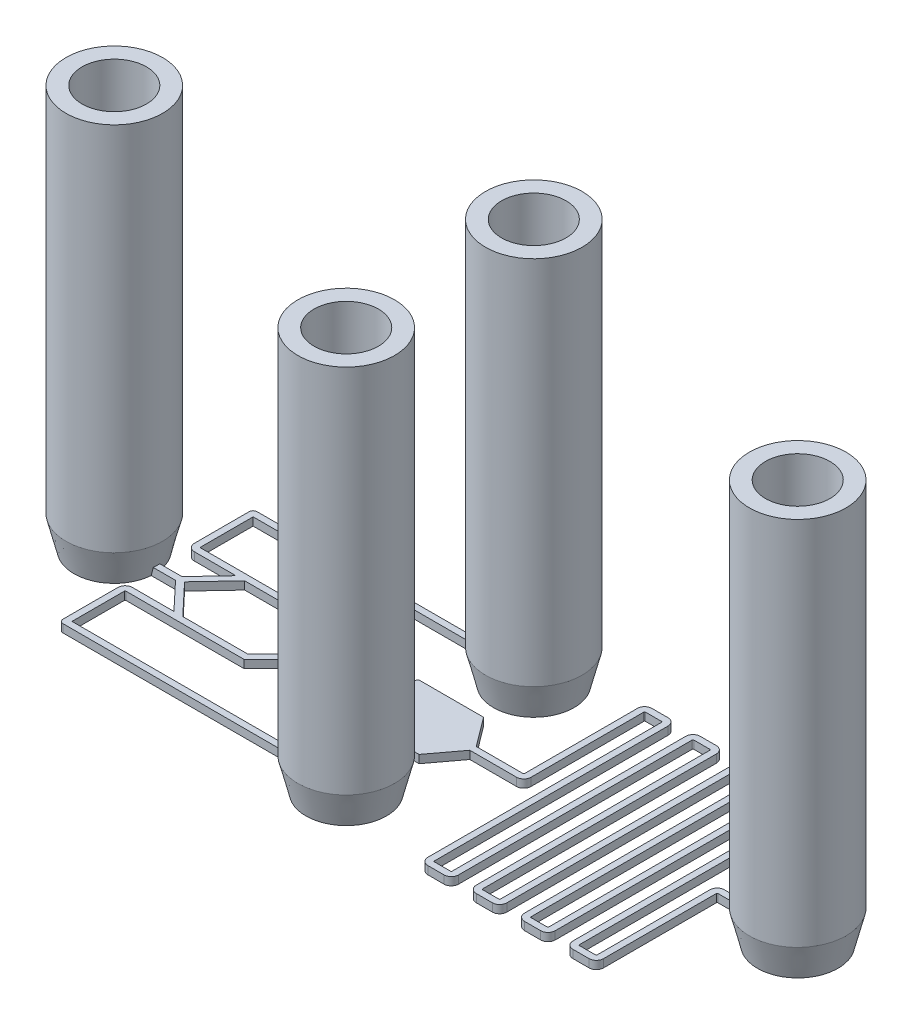
SolidWorks part; units mm, degrees
ref_plane "Front Plane" through (0, 0, 0) normal (0, 0, 1) x (1, 0, 0)
ref_plane "Top Plane" through (0, 0, 0) normal (0, 1, 0) x (1, 0, 0)
ref_plane "Right Plane" through (0, 0, 0) normal (1, 0, 0) x (0, 0, -1)
sketch "skelton" plane through (0, 0, 0) normal (0, 0, 1) x (1, 0, 0)
  line L0 (-100, 0) -> (100, 0) construction
  point P4 (0, 0)
sketch "Sketch2" plane through (0, 0, 0) normal (0, 1, 0) x (1, 0, 0)
  line L1 (-4, 4) -> (4, 4)
  line L3 (-4, -4) -> (4, -4)
  line L5 (-4, 4) -> (4, -4) construction
  line L6 (-4, -4) -> (4, 4) construction
  line L7 (-100, 0) -> (100, 0) construction
  line L9 (-6.7, 0.4) -> (-4, 4)
  line L10 (-6.7, -0.4) -> (-4, -4)
  line L11 (4, 4) -> (6.7, 0.4)
  line L12 (4, -4) -> (6.7, -0.4)
  line L13 (-31.8426, 11.2426) -> (2.6, 11.2426)
  line L15 (-31.8426, -12.0426) -> (2.6, -12.0426)
  line L16 (-6.7, 0.4) -> (-12.8343, 0.4)
  line L17 (-31.8426, 12.0426) -> (2.6, 12.0426)
  line L18 (-31.8426, -11.2426) -> (2.6, -11.2426)
  line L19 (-31.8426, 12.0426) -> (-32.1426, 12.0426)
  line L20 (-31.8426, -12.0426) -> (-32.1426, -12.0426)
  line L39 (-12.8343, 0.4) -> (-17.077, 4.6426)
  line L40 (-26.036, 3.8426) -> (-29.6589, 0) construction
  line L41 (-29.6589, 0) -> (-26.036, -3.8426) construction
  line L43 (-17.077, 4.6426) -> (-31.7426, 4.6426)
  line L44 (-31.8426, 4.7426) -> (-31.8426, 11.2426)
  line L45 (-13.5657, 0) -> (-17.4083, -3.8426)
  line L46 (-17.4083, -3.8426) -> (-25.4863, -3.8426)
  line L47 (-32.6426, -4.7426) -> (-32.6426, -11.5426)
  line L48 (-26.5858, 3.8426) -> (-31.7426, 3.8426)
  line L49 (-29.8315, -0.4) -> (-26.5858, -3.8426)
  line L50 (-29.8315, 0.4) -> (-37.8315, 0.4)
  line L51 (6.7, -0.4) -> (12.5, -0.4)
  line L52 (13.4, 14.5) -> (13.4, 0.5)
  line L53 (13.5, 14.6) -> (15.5, 14.6)
  line L54 (15.6, 14.5) -> (15.6, 0)
  line L55 (15.6, 0) -> (15.6, -14.5)
  line L56 (16.5, -15.4) -> (18.5, -15.4)
  line L57 (19.4, -14.5) -> (19.4, 14.5)
  line L58 (19.5, 14.6) -> (21.5, 14.6)
  line L59 (21.6, 14.5) -> (21.6, -14.5)
  line L60 (22.5, -15.4) -> (24.5, -15.4)
  line L61 (25.4, -14.5) -> (25.4, 14.5)
  line L62 (25.5, 14.6) -> (27.5, 14.6)
  line L63 (27.6, 14.5) -> (27.6, -14.5)
  line L64 (28.5, -15.4) -> (30.5, -15.4)
  line L65 (31.4, -14.5) -> (31.4, 14.5)
  line L66 (31.5, 14.6) -> (33.5, 14.6)
  line L67 (33.6, 14.5) -> (33.6, -14.5)
  line L68 (34.5, -15.4) -> (36.5, -15.4)
  line L69 (37.4, -14.5) -> (37.4, -0.5)
  line L70 (37.5, -0.4) -> (47, -0.4)
  line L71 (-6.7, -0.4) -> (-12.8343, -0.4)
  line L72 (-13.5657, 0) -> (-17.4083, 3.8426)
  line L73 (-17.4083, 3.8426) -> (-25.4863, 3.8426)
  line L74 (-32.6426, 4.7426) -> (-32.6426, 11.5426)
  line L75 (-12.8343, -0.4) -> (-17.077, -4.6426)
  line L76 (-17.077, -4.6426) -> (-31.7426, -4.6426)
  line L77 (-31.8426, -4.7426) -> (-31.8426, -11.2426)
  line L78 (-25.4863, 3.8426) -> (-29.1091, 0)
  line L79 (-29.1091, 0) -> (-25.4863, -3.8426)
  line L80 (-29.8315, -0.4) -> (-37.8315, -0.4)
  line L81 (6.7, 0.4) -> (12.5, 0.4)
  line L82 (12.6, 14.5) -> (12.6, 0.5)
  line L83 (13.5, 15.4) -> (15.5, 15.4)
  line L84 (16.4, 14.5) -> (16.4, 0)
  line L85 (16.4, 0) -> (16.4, -14.5)
  line L86 (16.5, -14.6) -> (18.5, -14.6)
  line L87 (18.6, -14.5) -> (18.6, 14.5)
  line L88 (19.5, 15.4) -> (21.5, 15.4)
  line L89 (22.4, 14.5) -> (22.4, -14.5)
  line L90 (22.5, -14.6) -> (24.5, -14.6)
  line L91 (24.6, -14.5) -> (24.6, 14.5)
  line L92 (25.5, 15.4) -> (27.5, 15.4)
  line L93 (28.4, 14.5) -> (28.4, -14.5)
  line L94 (28.5, -14.6) -> (30.5, -14.6)
  line L95 (30.6, -14.5) -> (30.6, 14.5)
  line L96 (31.5, 15.4) -> (33.5, 15.4)
  line L97 (34.4, 14.5) -> (34.4, -14.5)
  line L98 (34.5, -14.6) -> (36.5, -14.6)
  line L99 (36.6, -14.5) -> (36.6, -0.5)
  line L100 (37.5, 0.4) -> (47, 0.4)
  line L101 (-26.5858, 3.8426) -> (-29.8315, 0.4)
  line L103 (-25.6589, 4.2426) -> (-29.6589, 0) construction
  line L105 (-25.3678, 3.9682) -> (-29.3678, -0.2744) construction
  line L106 (-29.3678, 0.2744) -> (-25.3678, -3.9682) construction
  line L109 (-29.9499, -0.2744) -> (-25.9499, -4.517) construction
  line L110 (-29.6589, 0) -> (-25.6589, -4.2426) construction
  line L111 (-26.5858, -3.8426) -> (-31.7426, -3.8426)
  arc A5 (2.6, 11.2426) -> (2.6, 12.0426) centre (2.6, 11.6426) ccw
  arc A6 (2.6, -12.0426) -> (2.6, -11.2426) centre (2.6, -11.6426) ccw
  arc A7 (-37.8315, 0.4) -> (-37.8315, -0.4) centre (-37.8315, 0) ccw
  arc A8 (-32.1426, -12.0426) -> (-32.6426, -11.5426) centre (-32.1426, -11.5426) cw
  arc A9 (-32.6426, 11.5426) -> (-32.1426, 12.0426) centre (-32.1426, 11.5426) cw
  arc A20 (-31.7426, 4.6426) -> (-31.8426, 4.7426) centre (-31.7426, 4.7426) cw
  arc A21 (-31.7426, -3.8426) -> (-32.6426, -4.7426) centre (-31.7426, -4.7426) ccw
  arc A22 (12.5, -0.4) -> (13.4, 0.5) centre (12.5, 0.5) ccw
  arc A23 (13.4, 14.5) -> (13.5, 14.6) centre (13.5, 14.5) cw
  arc A24 (15.5, 14.6) -> (15.6, 14.5) centre (15.5, 14.5) cw
  arc A25 (15.6, -14.5) -> (16.5, -15.4) centre (16.5, -14.5) ccw
  arc A26 (18.5, -15.4) -> (19.4, -14.5) centre (18.5, -14.5) ccw
  arc A27 (19.4, 14.5) -> (19.5, 14.6) centre (19.5, 14.5) cw
  arc A28 (21.5, 14.6) -> (21.6, 14.5) centre (21.5, 14.5) cw
  arc A29 (21.6, -14.5) -> (22.5, -15.4) centre (22.5, -14.5) ccw
  arc A30 (24.5, -15.4) -> (25.4, -14.5) centre (24.5, -14.5) ccw
  arc A31 (25.4, 14.5) -> (25.5, 14.6) centre (25.5, 14.5) cw
  arc A32 (27.5, 14.6) -> (27.6, 14.5) centre (27.5, 14.5) cw
  arc A33 (27.6, -14.5) -> (28.5, -15.4) centre (28.5, -14.5) ccw
  arc A34 (30.5, -15.4) -> (31.4, -14.5) centre (30.5, -14.5) ccw
  arc A35 (31.4, 14.5) -> (31.5, 14.6) centre (31.5, 14.5) cw
  arc A36 (33.5, 14.6) -> (33.6, 14.5) centre (33.5, 14.5) cw
  arc A37 (33.6, -14.5) -> (34.5, -15.4) centre (34.5, -14.5) ccw
  arc A38 (36.5, -15.4) -> (37.4, -14.5) centre (36.5, -14.5) ccw
  arc A39 (37.4, -0.5) -> (37.5, -0.4) centre (37.5, -0.5) cw
  arc A40 (-31.7426, 3.8426) -> (-32.6426, 4.7426) centre (-31.7426, 4.7426) cw
  arc A41 (-31.7426, -4.6426) -> (-31.8426, -4.7426) centre (-31.7426, -4.7426) ccw
  arc A42 (12.5, 0.4) -> (12.6, 0.5) centre (12.5, 0.5) ccw
  arc A43 (12.6, 14.5) -> (13.5, 15.4) centre (13.5, 14.5) cw
  arc A44 (15.5, 15.4) -> (16.4, 14.5) centre (15.5, 14.5) cw
  arc A45 (16.4, -14.5) -> (16.5, -14.6) centre (16.5, -14.5) ccw
  arc A46 (18.5, -14.6) -> (18.6, -14.5) centre (18.5, -14.5) ccw
  arc A47 (18.6, 14.5) -> (19.5, 15.4) centre (19.5, 14.5) cw
  arc A48 (21.5, 15.4) -> (22.4, 14.5) centre (21.5, 14.5) cw
  arc A49 (22.4, -14.5) -> (22.5, -14.6) centre (22.5, -14.5) ccw
  arc A50 (24.5, -14.6) -> (24.6, -14.5) centre (24.5, -14.5) ccw
  arc A51 (24.6, 14.5) -> (25.5, 15.4) centre (25.5, 14.5) cw
  arc A52 (27.5, 15.4) -> (28.4, 14.5) centre (27.5, 14.5) cw
  arc A53 (28.4, -14.5) -> (28.5, -14.6) centre (28.5, -14.5) ccw
  arc A54 (30.5, -14.6) -> (30.6, -14.5) centre (30.5, -14.5) ccw
  arc A55 (30.6, 14.5) -> (31.5, 15.4) centre (31.5, 14.5) cw
  arc A56 (33.5, 15.4) -> (34.4, 14.5) centre (33.5, 14.5) cw
  arc A57 (34.4, -14.5) -> (34.5, -14.6) centre (34.5, -14.5) ccw
  arc A58 (36.5, -14.6) -> (36.6, -14.5) centre (36.5, -14.5) ccw
  arc A59 (36.6, -0.5) -> (37.5, 0.4) centre (37.5, -0.5) cw
  arc A67 (47, -0.4) -> (47, 0.4) centre (47, 0) ccw
  point P0 (0, 0)
  point P19 (-25.6589, 0)
  point P24 (13, 0)
  point P43 (37, -15)
  point P46 (34, -15)
  point P49 (31, -15)
  point P52 (28, -15)
  point P55 (25, -15)
  point P58 (22, -15)
  point P61 (19, -15)
  point P64 (16, -15)
  point P67 (13, 0)
  point P70 (-32.2426, -4.2426)
  point P73 (-32.2426, 4.2426)
  point P76 (37, 0)
  point P79 (34, 15)
  point P82 (31, 15)
  point P85 (28, 15)
  point P88 (25, 15)
  point P91 (22, 15)
  point P94 (19, 15)
  point P97 (16, 15)
  point P100 (13, 15)
  dimension "D11" = 0.5
  dimension "D14" = 0.5
  dimension "D1" = 3
  dimension "D2" = 3
  dimension "D4" = 3
  dimension "D5" = 3
  dimension "D6" = 3
  dimension "D7" = 3
  dimension "D8" = 3
  dimension "D9" = 3
  dimension "D17" = 8
  dimension "D18" = 30
  dimension "D20" = 0.4
  dimension "D21" = 0.4
extrude "skelton_extru" add sketch "Sketch2" along normal blind 1
ref_plane "Plane1" through (0, 0, -11.6426) normal (0, 0, 1) x (1, 0, 0)
sketch "Sketch3" plane through (0, 0, -11.6426) normal (0, 0, 1) x (1, 0, 0)
  line L0 (2.6, 0) -> (7.6, 0)
  line L1 (-100, 0) -> (100, 0) construction
  line L3 (2.6, 0) -> (2.6, 50)
  line L4 (2.6, 50) -> (8.6, 50)
  line L5 (8.6, 50) -> (8.6, 4)
  line L6 (8.6, 4) -> (7.6, 0)
  dimension "D1" = 5
  dimension "D3" = 50
  dimension "D4" = 6
revolve "Revolve1" add sketch "Sketch3" angle 360 about L3
ref_plane "Plane2" through (0, 0, 0) normal (0, 0, -1) x (-1, 0, 0)
sketch "Sketch4" plane through (0, 0, 0) normal (0, 0, -1) x (-1, 0, 0)
  line L0 (-47, 0) -> (-52, 0)
  line L1 (100, 0) -> (-100, 0) construction
  line L3 (-47, 0) -> (-47, 50)
  line L4 (-47, 50) -> (-53, 50)
  line L5 (-53, 50) -> (-53, 4)
  line L6 (-53, 4) -> (-52, 0)
  dimension "D1" = 5
  dimension "D3" = 50
  dimension "D4" = 6
revolve "Revolve2" add sketch "Sketch4" angle 360 about L3
ref_plane "Plane3" through (0, 0, 0) normal (0, 0, -1) x (-1, 0, 0)
sketch "Sketch5" plane through (0, 0, 0) normal (0, 0, -1) x (-1, 0, 0)
  line L0 (37.8315, 50) -> (37.8315, 0)
  line L1 (37.8315, 0) -> (42.8315, 0)
  line L2 (100, 0) -> (-100, 0) construction
  line L4 (37.8315, 50) -> (43.8315, 50)
  line L5 (43.8315, 50) -> (43.8315, 4)
  line L6 (43.8315, 4) -> (42.8315, 0)
  dimension "D1" = 50
  dimension "D2" = 5
  dimension "D4" = 6
revolve "Revolve3" add sketch "Sketch5" angle 360 about L0
ref_plane "Plane4" through (0, 0, 11.6426) normal (0, 0, 1) x (1, 0, 0)
sketch "Sketch6" plane through (0, 0, 11.6426) normal (0, 0, 1) x (1, 0, 0)
  line L0 (2.6, 0) -> (7.6, 0)
  line L1 (-100, 0) -> (100, 0) construction
  line L3 (2.6, 0) -> (2.6, 50)
  line L4 (2.6, 50) -> (8.6, 50)
  line L5 (8.6, 50) -> (8.6, 4)
  line L6 (8.6, 4) -> (7.6, 0)
  dimension "D1" = 5
  dimension "D3" = 50
  dimension "D4" = 6
revolve "Revolve4" add sketch "Sketch6" angle 360 about L3
sketch "Sketch8" plane through (0, 50, 0) normal (0, 1, 0) x (1, 0, 0)
  circle A0 centre (-37.8315, 0) radius 4
  circle A1 centre (2.6, 11.6426) radius 4
  circle A2 centre (2.6, -11.6426) radius 4
  circle A3 centre (47, 0) radius 4
  dimension "D1" = 8
  dimension "D2" = 8
  dimension "D3" = 8
  dimension "D4" = 8
extrude "Cut-Extrude1" cut sketch "Sketch8" against normal blind 45
